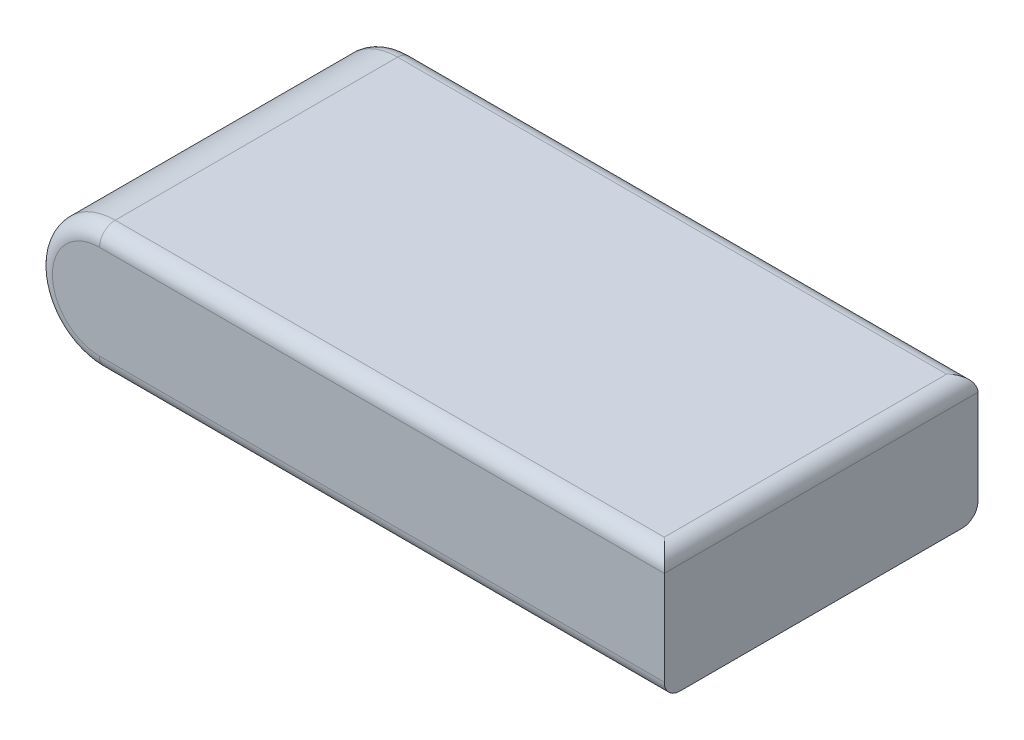
SolidWorks part; units mm, degrees
ref_plane "Спереди" through (0, 0, 0) normal (0, 0, 1) x (1, 0, 0)
ref_plane "Сверху" through (0, 0, 0) normal (0, 1, 0) x (1, 0, 0)
ref_plane "Справа" through (0, 0, 0) normal (1, 0, 0) x (0, 0, -1)
sketch "Эскиз1" plane through (0, 0, 0) normal (0, 0, 1) x (1, 0, 0)
  line L0 (-18, 4) -> (-18, -4) construction
  line L1 (18, -4) -> (-18, -4)
  line L2 (18, -4) -> (18, 4)
  line L3 (18, 4) -> (-18, 4)
  line L5 (18, -4) -> (-18, 4) construction
  line L6 (18, 4) -> (-18, -4) construction
  arc A0 (-18, -4) -> (-18, 4) centre (-18, 0) cw
  point P0 (0, 0)
  point P6 (-22, 0)
  point P8 (18, 0)
  dimension "D1" = 8
  dimension "D2" = 40
extrude "Бобышка-Вытянуть1" add sketch "Эскиз1" along normal blind 20
fillet "Скругление1" radius 1 7 edges at (0, -4, 20) (-22, 0, 20) (0, -4, 0) (-22, 0, 0) (18, 4, 10) (0, 4, 20) (0, 4, 0)
